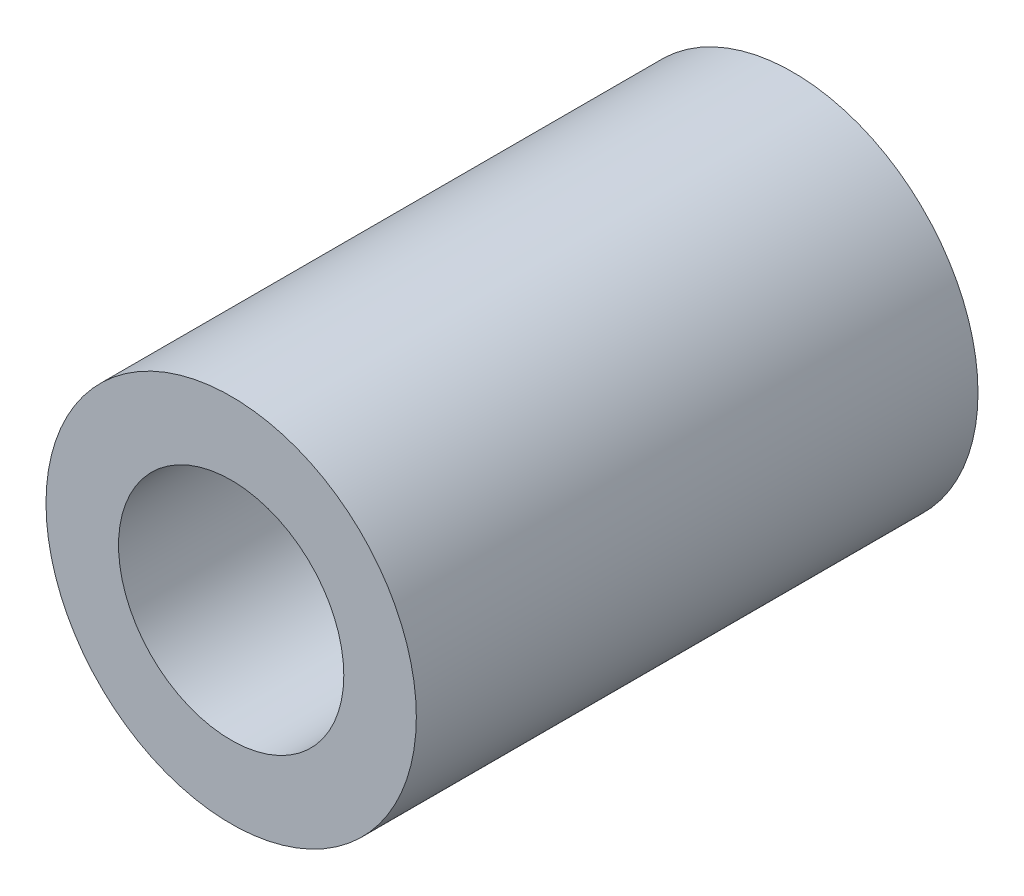
SolidWorks part; units mm, degrees
ref_plane "Front Plane" through (0, 0, 0) normal (0, 0, 1) x (1, 0, 0)
ref_plane "Top Plane" through (0, 0, 0) normal (0, 1, 0) x (1, 0, 0)
ref_plane "Right Plane" through (0, 0, 0) normal (1, 0, 0) x (0, 0, -1)
sketch "Sketch1" plane through (0, 0, 0) normal (0, 0, 1) x (1, 0, 0)
  circle A0 centre (0, 0) radius 1.825
  circle A1 centre (0, 0) radius 3
  dimension "D1" = 3.65
  dimension "D2" = 6
extrude "Boss-Extrude1" add sketch "Sketch1" along normal blind 9.1
